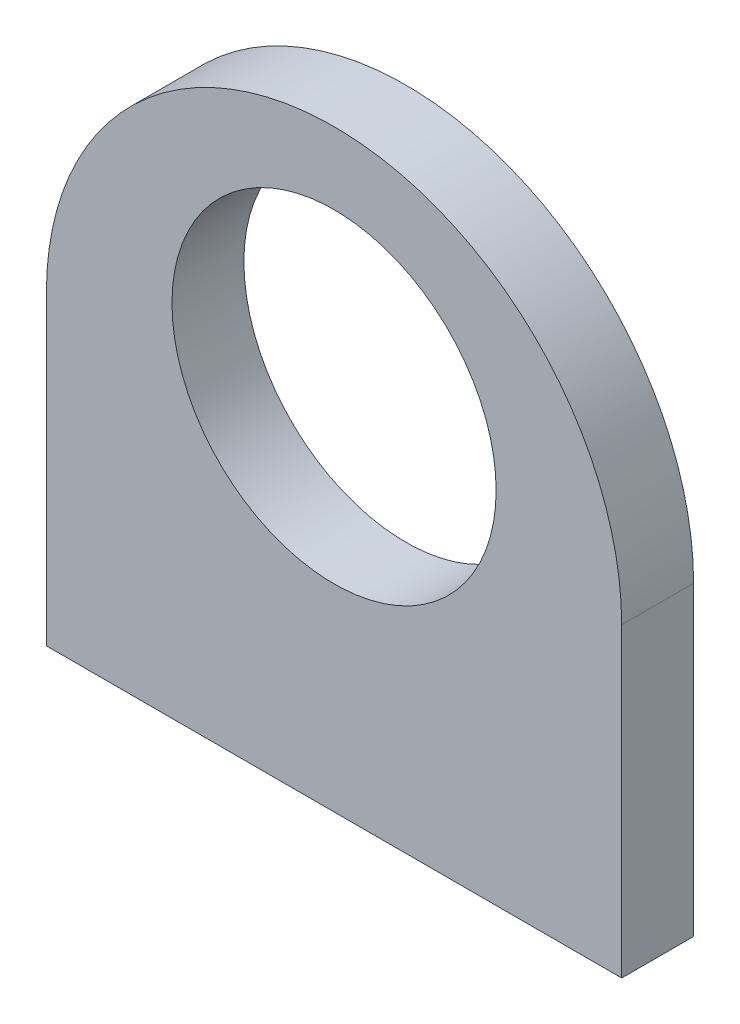
SolidWorks part; units mm, degrees
material "6061 Alloy"
ref_plane "Front" through (0, 0, 0) normal (0, 0, 1) x (1, 0, 0)
ref_plane "Top" through (0, 0, 0) normal (0, 1, 0) x (1, 0, 0)
ref_plane "Right" through (0, 0, 0) normal (1, 0, 0) x (0, 0, -1)
sketch "Sketch1" plane through (0, 0, 0) normal (0, 0, 1) x (1, 0, 0)
  line L0 (50.8, 31.75) -> (0, 31.75) construction
  line L1 (0, 0) -> (50.8, 0)
  line L2 (0, 0) -> (0, 27.0129)
  line L4 (50.8, 0) -> (50.8, 27.0129)
  circle A0 centre (25.4, 31.75) radius 14.3129
  arc A1 (50.8, 27.0129) -> (0, 27.0129) centre (25.4, 27.0129) ccw
  point P7 (29.3015, 13.8368)
  point P10 (25.4, 31.75)
  point P11 (25.4, 25.5031)
  point P12 (0, 0)
  dimension "D3" = 28.6258
  dimension "D4" = 6.35
  dimension "D1" = 50.8
  dimension "D2" = 31.75
extrude "Boss-Extrude1" add sketch "Sketch1" along normal blind 6.35
